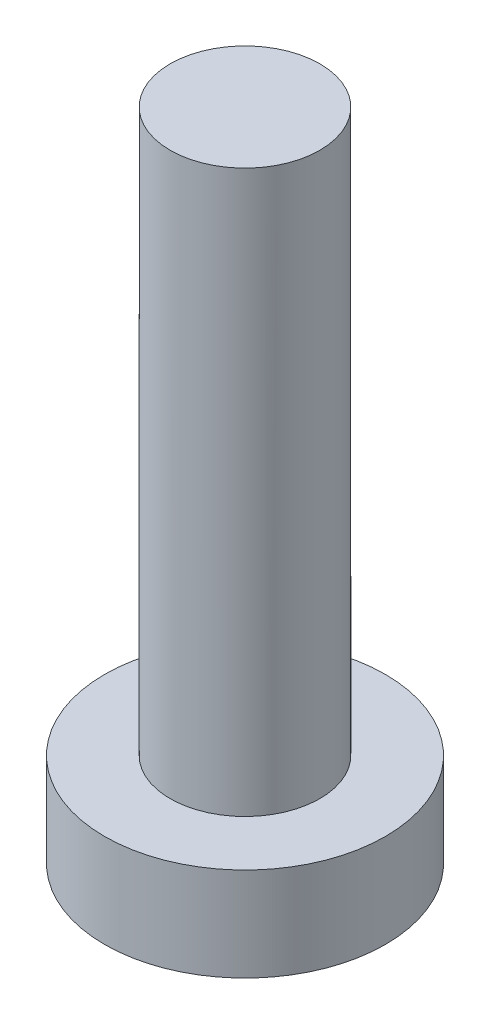
SolidWorks part; units mm, degrees
ref_plane "Front Plane" through (0, 0, 0) normal (0, 0, 1) x (1, 0, 0)
ref_plane "Top Plane" through (0, 0, 0) normal (0, 1, 0) x (1, 0, 0)
ref_plane "Right Plane" through (0, 0, 0) normal (1, 0, 0) x (0, 0, -1)
sketch "Sketch2" plane through (0, 0, 0) normal (0, 1, 0) x (1, 0, 0)
  circle A0 centre (0, 0) radius 0.8
  dimension "D1" = 1.6
extrude "Boss-Extrude1" add sketch "Sketch2" along normal blind 6
sketch "Sketch3" plane through (0, 0, 0) normal (0, -1, 0) x (1, 0, 0)
  circle A0 centre (0, 0) radius 1.5
  dimension "D1" = 3
extrude "Boss-Extrude2" add sketch "Sketch3" along normal blind 1
